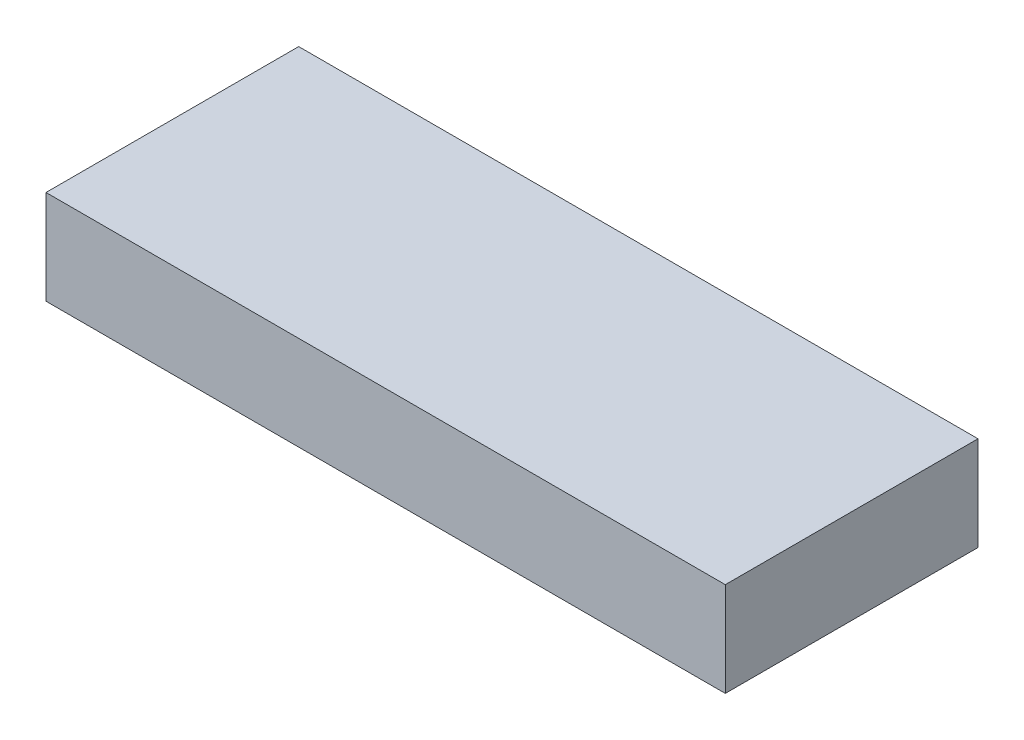
SolidWorks part; units mm, degrees
ref_plane "Front Plane" through (0, 0, 0) normal (0, 0, 1) x (1, 0, 0)
ref_plane "Top Plane" through (0, 0, 0) normal (0, 1, 0) x (1, 0, 0)
ref_plane "Right Plane" through (0, 0, 0) normal (1, 0, 0) x (0, 0, -1)
sketch "Sketch1" plane through (0, 0, 0) normal (0, 1, 0) x (1, 0, 0)
  line L1 (0, 0) -> (38.1, 0)
  line L2 (0, 0) -> (0, 14.1732)
  line L3 (0, 14.1732) -> (38.1, 14.1732)
  line L4 (38.1, 0) -> (38.1, 14.1732)
  dimension "D1" = 38.1
  dimension "D2" = 14.1732
extrude "Boss-Extrude1" add sketch "Sketch1" along normal blind 5.2832
